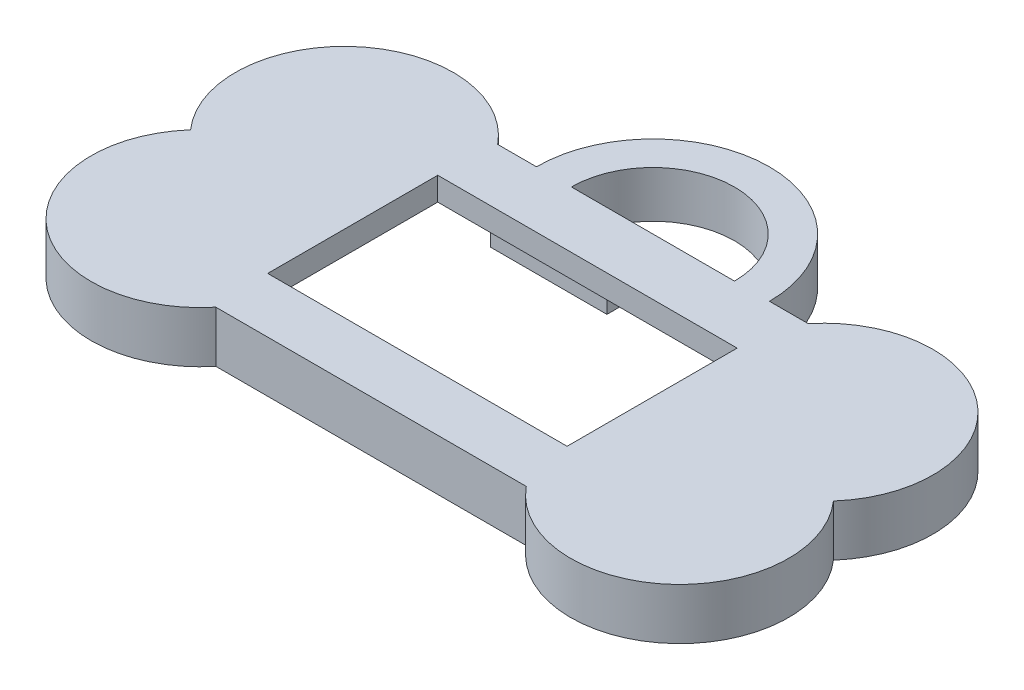
SolidWorks part; units mm, degrees
ref_plane "Front Plane" through (0, 0, 0) normal (0, 0, 1) x (1, 0, 0)
ref_plane "Top Plane" through (0, 0, 0) normal (0, 1, 0) x (1, 0, 0)
ref_plane "Right Plane" through (0, 0, 0) normal (1, 0, 0) x (0, 0, -1)
sketch "Sketch1" plane through (0, 0, 0) normal (0, 1, 0) x (1, 0, 0)
  line L0 (13.62, 14.1132) -> (-22.83, 14.1122)
  line L1 (-22.829, -11.5408) -> (13.621, -11.5398)
  line L2 (14.8977, -12.0587) -> (23.0691, -12.0587)
  line L3 (23.0691, -12.0587) -> (23.0691, -7.4786)
  line L4 (-23.0703, -12.0587) -> (-31.1593, -12.0467)
  line L5 (-31.1593, -12.0467) -> (-31.1593, -7.2967)
  line L6 (-23.0703, -12.0587) -> (-23.0703, 4.8825)
  line L7 (-36.0683, 1.2763) -> (-36.0683, 6.3059)
  line L8 (-23.0703, 4.8825) -> (-27.0784, 4.8825)
  line L9 (-23.0703, 4.8825) -> (-23.0703, -4.0811)
  line L10 (-23.0703, -4.0811) -> (-27.0784, -4.0811)
  line L11 (-27.0784, 4.8825) -> (-27.0784, -4.0811)
  line L12 (-23.0703, -8.5283) -> (17.2634, -8.5283)
  line L13 (-23.0703, -8.5283) -> (-23.0703, 10.8014)
  line L14 (-23.0703, 10.8014) -> (17.2634, 10.8014)
  line L15 (17.2634, -8.5283) -> (17.2634, 10.8014)
  line L16 (-36.0683, 6.3059) -> (-39.1176, 6.3059)
  line L17 (-39.1176, 6.3059) -> (-27.0784, 6.3059)
  line L18 (-27.0784, 6.3059) -> (-27.0784, 4.8825)
  line L19 (13.3147, -7.6038) -> (-17.9273, -7.6038)
  line L20 (13.3147, -7.6038) -> (13.3147, 10.1762)
  line L21 (13.3147, 10.1762) -> (-17.9273, 10.1762)
  line L22 (-17.9273, -7.6038) -> (-17.9273, 10.1762)
  line L23 (-21.5298, -14.0808) -> (12.3218, -14.0799)
  line L24 (12.3208, 16.6531) -> (-21.5307, 16.6522)
  line L25 (-4.605, 14.1127) -> (-4.605, 11.6371)
  line L26 (-4.605, 11.6371) -> (-17.3049, 11.6371)
  line L27 (-17.3049, 11.6371) -> (-17.3049, 14.1123)
  line L28 (-17.3049, 14.1123) -> (-4.605, 14.1127)
  line L29 (-21.5298, -11.5408) -> (-21.5298, -9.0301)
  line L30 (-21.5298, -9.0301) -> (-10.955, -9.0301)
  line L31 (-10.955, -9.0301) -> (-10.955, -11.5405)
  line L32 (-10.955, -11.5405) -> (-21.5298, -11.5408)
  line L33 (12.3218, -11.5399) -> (12.3218, -9.0301)
  line L34 (12.3218, -9.0301) -> (1.6405, -9.0301)
  line L35 (1.6405, -9.0301) -> (1.6405, -11.5402)
  line L36 (1.6405, -11.5402) -> (12.0981, -11.5399)
  line L37 (12.0981, -11.5399) -> (12.3218, -11.5399)
  arc A0 (-22.83, 14.1122) -> (-35.783, 1.2862) centre (-30.7456, 9.1525) ccw
  arc A1 (-35.783, 1.2862) -> (-22.829, -11.5408) centre (-30.7447, -6.5803) ccw
  arc A2 (13.621, -11.5398) -> (26.574, 1.2862) centre (21.5366, -6.5802) ccw
  arc A3 (26.574, 1.2862) -> (13.62, 14.1132) centre (21.5357, 9.1526) ccw
  circle A4 centre (-31.1499, -9.0301) radius 1.7334
  circle A5 centre (23.0691, -9.2145) radius 1.7334
  circle A6 centre (-8.7574, -9.2294) radius 0.7493
  circle A7 centre (-0.568, -9.2548) radius 0.7493
  circle A8 centre (-33.4016, 4.3213) radius 0.0119
  circle A9 centre (-33.751, 4.2072) radius 0.3556
  circle A10 centre (-31.846, 4.2072) radius 0.3556
  circle A11 centre (-27.655, 4.9692) radius 0.3576
  circle A12 centre (-36.037, -3.4128) radius 0.3556
  arc A13 (-21.5307, 16.6522) -> (-39.6493, 1.286) centre (-30.7456, 9.1525) ccw
  arc A14 (-39.6493, 1.286) -> (-21.5298, -14.0808) centre (-30.7447, -6.5803) ccw
  arc A15 (12.3218, -14.0799) -> (30.4404, 1.2863) centre (21.5366, -6.5802) ccw
  arc A16 (30.4404, 1.2863) -> (12.3208, 16.6531) centre (21.5357, 9.1526) ccw
  arc A17 (-13.4949, 16.6524) -> (4.2851, 16.6529) centre (-4.6049, 16.6527) cw
  arc A18 (-17.3049, 16.6523) -> (8.0951, 16.653) centre (-4.6049, 16.6527) cw
  dimension "D1" = 2.54
extrude "Boss-Extrude1" add sketch "Sketch1" along normal blind 2.54
sketch "Sketch3" plane through (0, 2.54, 0) normal (0, 1, 0) x (1, 0, 0)
  line L0 (-13.4949, 16.6524) -> (4.2851, 16.6529)
  line L1 (10.755, 10.472) -> (-21.8857, 10.472)
  line L2 (10.755, 10.472) -> (10.755, -8.0664)
  line L3 (12.3208, 16.6531) -> (8.0951, 16.653)
  line L4 (-17.3049, 16.6523) -> (-21.5307, 16.6522)
  line L5 (-21.5298, -14.0808) -> (12.3218, -14.0799)
  line L6 (12.3208, 16.6531) -> (8.0951, 16.653)
  line L7 (-17.3049, 16.6523) -> (-21.5307, 16.6522)
  line L8 (-21.5298, -14.0808) -> (12.3218, -14.0799)
  line L9 (10.755, -8.0664) -> (-21.8857, -8.0664)
  line L10 (-21.8857, 10.472) -> (-21.8857, -8.0664)
  arc A1 (-13.4949, 16.6524) -> (4.2851, 16.6529) centre (-4.6049, 16.6527) cw
  arc A2 (4.2851, 16.6529) -> (-13.4949, 16.6524) centre (-4.6049, 16.6527) ccw construction
  arc A5 (12.3218, -14.0799) -> (30.4404, 1.2863) centre (21.5366, -6.5802) ccw
  arc A6 (30.4404, 1.2863) -> (12.3208, 16.6531) centre (21.5357, 9.1526) ccw
  arc A7 (8.0951, 16.653) -> (-17.3049, 16.6523) centre (-4.6049, 16.6527) ccw
  arc A8 (-21.5307, 16.6522) -> (-39.6493, 1.286) centre (-30.7456, 9.1525) ccw
  arc A9 (-39.6493, 1.286) -> (-21.5298, -14.0808) centre (-30.7447, -6.5803) ccw
  arc A10 (12.3218, -14.0799) -> (30.4404, 1.2863) centre (21.5366, -6.5802) ccw
  arc A11 (30.4404, 1.2863) -> (12.3208, 16.6531) centre (21.5357, 9.1526) ccw
  arc A12 (8.0951, 16.653) -> (-17.3049, 16.6523) centre (-4.6049, 16.6527) ccw
  arc A13 (-21.5307, 16.6522) -> (-39.6493, 1.286) centre (-30.7456, 9.1525) ccw
  arc A14 (-39.6493, 1.286) -> (-21.5298, -14.0808) centre (-30.7447, -6.5803) ccw
  dimension "D1" = 0
extrude "Boss-Extrude3" add sketch "Sketch3" along normal blind 2.54 contours A10 A11 L6 A12 L7 A13 A14 L8 | L0 A1 | L2 L1 L10 L9
sketch "Sketch4" plane through (0, 0, 0) normal (0, -1, 0) x (1, 0, 0)
  line L0 (8.0951, -16.653) -> (-17.3049, -16.6523)
  line L1 (13.3447, 12.0478) -> (-22.5526, 12.0488)
  line L2 (-22.5536, -14.6202) -> (-17.3049, -14.6203)
  line L3 (12.3218, 14.0799) -> (-21.5298, 14.0808)
  line L4 (-21.5307, -16.6522) -> (-17.3049, -16.6523)
  line L5 (8.0951, -16.653) -> (12.3208, -16.6531)
  line L6 (12.3218, 14.0799) -> (-21.5298, 14.0808)
  line L7 (-21.5307, -16.6522) -> (-17.3049, -16.6523)
  line L8 (8.0951, -16.653) -> (12.3208, -16.6531)
  line L9 (8.0951, -14.621) -> (-17.3049, -14.6203)
  line L10 (8.0951, -14.621) -> (13.3437, -14.6212)
  line L11 (13.3437, -14.6212) -> (13.3447, 12.0478)
  line L12 (-22.5536, -14.6202) -> (-22.5526, 12.0488)
  arc A0 (13.3437, -14.6212) -> (27.4631, -1.2862) centre (21.5357, -9.1526) ccw
  arc A1 (27.4631, -1.2862) -> (13.3447, 12.0478) centre (21.5366, 6.5802) ccw
  arc A2 (-22.5526, 12.0488) -> (-36.6721, -1.2861) centre (-30.7447, 6.5803) ccw
  arc A3 (-36.6721, -1.2861) -> (-22.5536, -14.6202) centre (-30.7456, -9.1525) ccw
  arc A5 (30.4404, -1.2863) -> (12.3218, 14.0799) centre (21.5366, 6.5802) ccw
  arc A6 (-21.5298, 14.0808) -> (-39.6493, -1.286) centre (-30.7447, 6.5803) ccw
  arc A7 (-39.6493, -1.286) -> (-21.5307, -16.6522) centre (-30.7456, -9.1525) ccw
  arc A8 (-17.3049, -16.6523) -> (8.0951, -16.653) centre (-4.6049, -16.6527) ccw
  arc A9 (12.3208, -16.6531) -> (30.4404, -1.2863) centre (21.5357, -9.1526) ccw
  arc A10 (30.4404, -1.2863) -> (12.3218, 14.0799) centre (21.5366, 6.5802) ccw
  arc A11 (-21.5298, 14.0808) -> (-39.6493, -1.286) centre (-30.7447, 6.5803) ccw
  arc A12 (-39.6493, -1.286) -> (-21.5307, -16.6522) centre (-30.7456, -9.1525) ccw
  arc A14 (12.3208, -16.6531) -> (30.4404, -1.2863) centre (21.5357, -9.1526) ccw
  line M18 (-13.4949, -16.6524) -> (4.2851, -16.6529)
  arc M40 (30.4404, -1.2863) -> (12.3218, 14.0799) centre (21.5366, 6.5802) ccw
  line M41 (12.3218, 14.0799) -> (-21.5298, 14.0808)
  arc M42 (-21.5298, 14.0808) -> (-39.6493, -1.286) centre (-30.7447, 6.5803) ccw
  arc M43 (-39.6493, -1.286) -> (-21.5307, -16.6522) centre (-30.7456, -9.1525) ccw
  line M44 (-21.5307, -16.6522) -> (-17.3049, -16.6523)
  line M46 (8.0951, -16.653) -> (12.3208, -16.6531)
  arc M47 (12.3208, -16.6531) -> (30.4404, -1.2863) centre (21.5357, -9.1526) ccw
  dimension "D1" = 0
  dimension "D2" = 2.032
extrude "Boss-Extrude5" add sketch "Sketch4" along normal blind 0.508 contours L0 A3 A2 L1 A1 A0 L10 L9 L2 M46 M47 M40 M41 M42 M43 M44 M18
